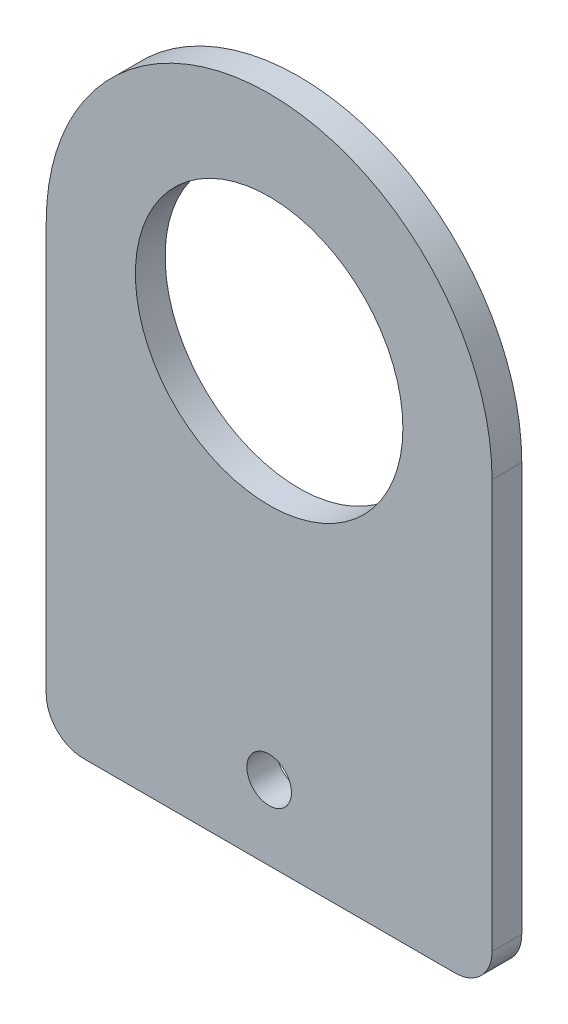
SolidWorks part; units mm, degrees
ref_plane "Front Plane" through (0, 0, 0) normal (0, 0, 1) x (1, 0, 0)
ref_plane "Top Plane" through (0, 0, 0) normal (0, 1, 0) x (1, 0, 0)
ref_plane "Right Plane" through (0, 0, 0) normal (1, 0, 0) x (0, 0, -1)
sketch "Sketch3" plane through (0, 0, 0) normal (0, 0, 1) x (1, 0, 0)
  line L0 (75.5, 79.5) -> (75.5, 94.5)
  line L1 (105.5, 67) -> (105.5, 94.5)
  line L2 (75.5, 67) -> (75.5, 79.5)
  line L3 (78, 64.5) -> (103, 64.5)
  circle A0 centre (90.5, 94.5) radius 9
  arc A1 (105.5, 94.5) -> (75.5, 94.5) centre (90.5, 94.5) ccw
  circle A2 centre (90.5, 69.5) radius 1.5
  arc A3 (103, 64.5) -> (105.5, 67) centre (103, 67) ccw
  arc A4 (75.5, 67) -> (78, 64.5) centre (78, 67) ccw
extrude "Boss-Extrude1" add sketch "Sketch3" along normal blind 2
